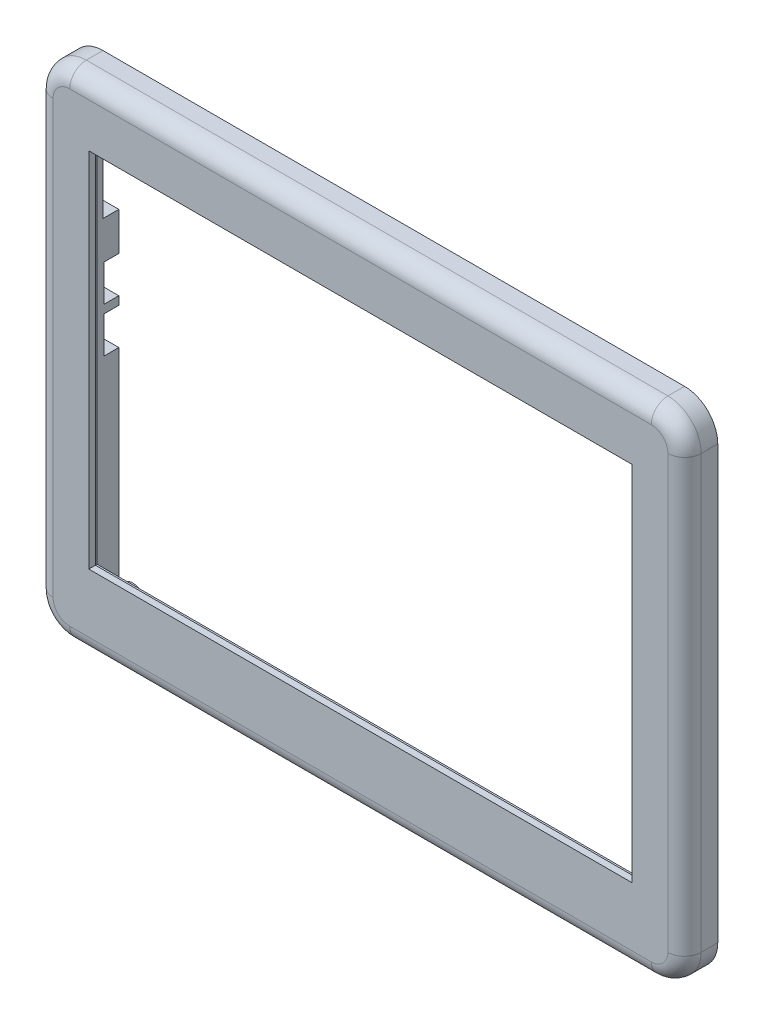
SolidWorks part; units mm, degrees
material "Alliage 2018"
ref_plane "Plan de face" through (0, 0, 0) normal (0, 0, 1) x (1, 0, 0)
ref_plane "Plan de dessus" through (0, 0, 0) normal (0, 1, 0) x (1, 0, 0)
ref_plane "Plan de droite" through (0, 0, 0) normal (1, 0, 0) x (0, 0, -1)
sketch "Esquisse1" plane through (0, 0, 0) normal (0, 0, 1) x (1, 0, 0)
  line L0 (0, 59.7179) -> (0, -59.7179) construction
  line L1 (-74.4642, 58.5) -> (74.4642, 58.5)
  line L2 (-82.5, 58.5) -> (-82.5, -58.5)
  line L3 (-74.4642, -58.5) -> (74.4642, -58.5)
  line L4 (82.5, 58.5) -> (82.5, -58.5)
  line L5 (-82.5, 58.5) -> (82.5, -58.5) construction
  line L6 (-82.5, -58.5) -> (82.5, 58.5) construction
  line L7 (-82, 57) -> (82, 57)
  line L8 (-82, 57) -> (-82, -52.5)
  line L9 (-82, -52.5) -> (82, -52.5)
  line L10 (82, 57) -> (82, -52.5)
  line L12 (-82.5, 58.5) -> (-82.5, 63.01)
  line L13 (-78.51, 67) -> (-78.4542, 67)
  line L14 (-74.4642, 58.5) -> (-74.4642, 63.01)
  line L15 (82.5, 0) -> (-82.5, 0) construction
  line L16 (74.4642, 58.5) -> (74.4642, 63.01)
  line L17 (78.51, 67) -> (78.4542, 67)
  line L18 (82.5, 58.5) -> (82.5, 63.01)
  line L19 (-81.5, -52) -> (81.5, -52)
  line L20 (-81.5, -52) -> (-81.5, 56.5)
  line L21 (82.5, -58.5) -> (82.5, -63.01)
  line L22 (78.51, -67) -> (78.4542, -67)
  line L23 (74.4642, -58.5) -> (74.4642, -63.01)
  line L24 (-74.4642, -58.5) -> (-74.4642, -63.01)
  line L25 (-78.51, -67) -> (-78.4542, -67)
  line L26 (-82.5, -58.5) -> (-82.5, -63.01)
  line L27 (-81.5, 56.5) -> (81.5, 56.5)
  line L28 (81.5, -52) -> (81.5, 56.5)
  line L29 (87.5, -75) -> (-87.5, -75)
  line L30 (97.5, -65) -> (97.5, 65)
  line L31 (87.5, 75) -> (-87.5, 75)
  line L32 (-97.5, -65) -> (-97.5, 65)
  line L33 (97.5, -75) -> (-97.5, 75) construction
  line L34 (97.5, 75) -> (-97.5, -75) construction
  circle A0 centre (-78.5, 62.75) radius 1.6
  arc A1 (-78.4542, 67) -> (-74.4642, 63.01) centre (-78.4542, 63.01) cw
  arc A2 (-82.5, 63.01) -> (-78.51, 67) centre (-78.51, 63.01) cw
  arc A3 (82.5, 63.01) -> (78.51, 67) centre (78.51, 63.01) ccw
  arc A4 (78.4542, 67) -> (74.4642, 63.01) centre (78.4542, 63.01) ccw
  circle A5 centre (78.5, 62.75) radius 1.6
  circle A6 centre (78.5, -62.75) radius 1.6
  arc A7 (78.4542, -67) -> (74.4642, -63.01) centre (78.4542, -63.01) cw
  arc A8 (82.5, -63.01) -> (78.51, -67) centre (78.51, -63.01) cw
  arc A9 (-82.5, -63.01) -> (-78.51, -67) centre (-78.51, -63.01) ccw
  arc A10 (-78.4542, -67) -> (-74.4642, -63.01) centre (-78.4542, -63.01) ccw
  circle A11 centre (-78.5, -62.75) radius 1.6
  arc A12 (97.5, 65) -> (87.5, 75) centre (87.5, 65) ccw
  arc A13 (87.5, -75) -> (97.5, -65) centre (87.5, -65) ccw
  arc A14 (-87.5, -75) -> (-97.5, -65) centre (-87.5, -65) cw
  arc A15 (-97.5, 65) -> (-87.5, 75) centre (-87.5, 65) cw
  point P0 (0, 0)
  point P21 (0, 0)
  point P34 (82.5, 67)
  point P35 (74.5, 67)
  point P45 (74.5, -67)
  point P46 (82.5, -67)
  point P56 (-82.5, -67)
  point P57 (-74.5, -67)
  dimension "D5" = 4.25
  dimension "D6" = 3.99
  dimension "D15" = 10
  dimension "D1" = 117
  dimension "D2" = 165
  dimension "D3" = 195
  dimension "D4" = 150
  dimension "D7" = 1.5
  dimension "D8" = 6
  dimension "D9" = 0.5
  dimension "D10" = 0.5
  dimension "D11" = 0.5
  dimension "D12" = 0.5
  dimension "D13" = 0.5
  dimension "D14" = 0.5
extrude "Boss.-Extru.1" add sketch "Esquisse1" along normal blind 10 contours L31 A15 L32 A14 L29 A13 L30 A12
sketch "Esquisse2" plane through (0, 0, 10) normal (0, 0, 1) x (1, 0, 0)
  line L14 (81.75, -52.25) -> (81.75, 56.75)
  line L15 (-81.75, -52.25) -> (81.75, -52.25)
  line L16 (-81.75, 56.75) -> (-81.75, -52.25)
  line L17 (81.75, 56.75) -> (-81.75, 56.75)
  line L18 (81.75, -52.25) -> (81.75, 56.75)
  line L19 (-81.75, -52.25) -> (81.75, -52.25)
  line L20 (-81.75, 56.75) -> (-81.75, -52.25)
  line L21 (81.75, 56.75) -> (-81.75, 56.75)
  dimension "D1" = 0.25
extrude "Enlèv. mat.-Extru.1" cut sketch "Esquisse2" against normal blind 10
sketch "Esquisse3" plane through (0, 0, 0) normal (0, 0, -1) x (-1, 0, 0)
  line L14 (82.25, -52.75) -> (82.25, 57.25)
  line L15 (-82.25, -52.75) -> (82.25, -52.75)
  line L16 (-82.25, 57.25) -> (-82.25, -52.75)
  line L17 (82.25, 57.25) -> (-82.25, 57.25)
  line L18 (82.25, -52.75) -> (82.25, 57.25)
  line L19 (-82.25, -52.75) -> (82.25, -52.75)
  line L20 (-82.25, 57.25) -> (-82.25, -52.75)
  line L21 (82.25, 57.25) -> (-82.25, 57.25)
  dimension "D1" = 0.25
extrude "Enlèv. mat.-Extru.2" cut sketch "Esquisse3" against normal blind 8
sketch "Esquisse4" plane through (0, 0, 0) normal (0, 0, -1) x (-1, 0, 0)
  line L0 (-74.3058, -63.01) -> (74.3058, -63.01)
  line L1 (0, 58.5) -> (0, 0) construction
  line L2 (74.4642, 58.5) -> (-74.4642, 58.5) construction
  line L3 (0, 0) -> (82.5754, 0) construction
  line L6 (-82.7142, 63.01) -> (-82.7142, -63.01)
  line L10 (82.7142, 63.01) -> (82.7142, -63.01)
  line L11 (-74.3058, 63.01) -> (74.3058, 63.01)
  arc A0 (74.3058, 63.01) -> (82.7142, 63.01) centre (78.51, 63.01) cw
  arc A1 (-74.3058, -63.01) -> (-82.7142, -63.01) centre (-78.51, -63.01) cw
  arc A2 (74.3058, -63.01) -> (82.7142, -63.01) centre (78.51, -63.01) ccw
  arc A19 (-74.3058, 63.01) -> (-82.7142, 63.01) centre (-78.51, 63.01) ccw
extrude "Enlèv. mat.-Extru.3" cut sketch "Esquisse4" against normal blind 7
sketch "Esquisse5" plane through (0, 0, 7) normal (0, 0, -1) x (-1, 0, 0)
  circle A0 centre (-78.5, 62.75) radius 1.25
  circle A1 centre (78.5, 62.75) radius 1.25
  circle A2 centre (78.5, -62.75) radius 1.25
  circle A3 centre (-78.5, -62.75) radius 1.25
  circle A4 centre (-78.5, -62.75) radius 3.5
  circle A5 centre (78.5, -62.75) radius 3.5
  circle A6 centre (78.5, 62.75) radius 3.5
  circle A7 centre (-78.5, 62.75) radius 3.5
  dimension "D1" = 2.5
  dimension "D2" = 7
  dimension "D3" = 7
extrude "Boss.-Extru.2" add sketch "Esquisse5" along normal up to surface (7 mm away) up to face at (0, 0, 0)
fillet "Congé1" radius 5 8 edges at (-97.5, 0, 10) (-94.5711, -72.0711, 10) (0, -75, 10) (94.5711, -72.0711, 10) (97.5, 0, 10) (94.5711, 72.0711, 10) (0, 75, 10) (-94.5711, 72.0711, 10)
sketch "Esquisse6" plane through (0, 0, 0) normal (1, 0, 0) x (0, 0, -1)
  line L0 (4.33, 46.5) -> (-1.8, 46.5205) construction
  line L1 (4.33, 54) -> (-1.8, 54) construction
  line L2 (4.33, 54) -> (4.33, 39) construction
  line L3 (4.33, 39) -> (-1.8, 39) construction
  line L4 (-1.8, 54) -> (-1.8, 39) construction
  line L5 (-10, 65) -> (-10, -65) construction
  line L7 (-5, 75) -> (0, 75) construction
  line L8 (-4.8, 57) -> (7.33, 57)
  line L9 (-4.8, 57) -> (-4.8, 36)
  line L10 (-4.8, 36) -> (7.33, 36)
  line L11 (0.8, 19) -> (-1.8, 19) construction
  line L12 (0.8, 5.5) -> (-1.8, 5.5) construction
  line L13 (-4.5, 24.5) -> (3.5, 24.5)
  line L14 (-4.5, 24.5) -> (-4.5, 13.5)
  line L15 (-4.5, 13.5) -> (3.5, 13.5)
  line L16 (3.5, 24.5) -> (3.5, 13.5)
  line L17 (-4.5, 24.5) -> (3.5, 13.5) construction
  line L18 (-4.5, 13.5) -> (3.5, 24.5) construction
  line L19 (-0.5, 19) -> (-0.5, 5.5) construction
  line L20 (10, 0) -> (-10, 0) construction
  line L21 (-4.5, 11) -> (3.5, 11)
  line L22 (-4.5, 11) -> (-4.5, 0)
  line L23 (-4.5, 0) -> (3.5, 0)
  line L24 (3.5, 11) -> (3.5, 0)
  line L25 (-4.5, 11) -> (3.5, 0) construction
  line L26 (-4.5, 0) -> (3.5, 11) construction
  line L27 (7.33, 57) -> (7.33, 36)
  point P6 (1.265, 46.5102)
  point P7 (1.265, 39)
  point P13 (-0.5, 19)
  dimension "D1" = 15
  dimension "D2" = 6.13
  dimension "D3" = 8
  dimension "D4" = 11
  dimension "D5" = 11
  dimension "D6" = 8
  dimension "D7" = 8.2
  dimension "D8" = 21
  dimension "D9" = 3
  dimension "D10" = 3
  dimension "D11" = 3
  dimension "D12" = 3
extrude "Enlèv. mat.-Extru.4" cut sketch "Esquisse6" against normal up to surface (97.5 mm away) up to face at (-97.5, 0, 2.5)
